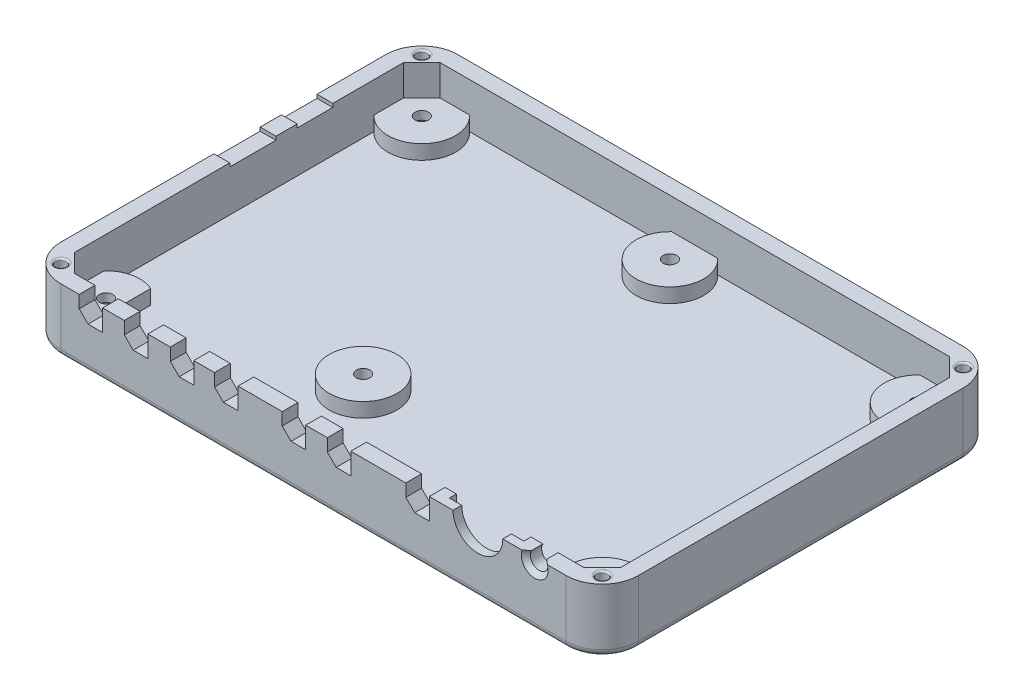
SolidWorks part; units mm, degrees
ref_plane "Front Plane" through (0, 0, 0) normal (0, 0, 1) x (1, 0, 0)
ref_plane "Top Plane" through (0, 0, 0) normal (0, 1, 0) x (1, 0, 0)
ref_plane "Right Plane" through (0, 0, 0) normal (1, 0, 0) x (0, 0, -1)
sketch "Sketch1" plane through (0, 0, 0) normal (0, 1, 0) x (1, 0, 0)
  line L1 (-71.12, 55.88) -> (71.12, 55.88)
  line L2 (-81.28, 45.72) -> (-81.28, -45.72)
  line L3 (-71.12, -55.88) -> (71.12, -55.88)
  line L4 (81.28, 45.72) -> (81.28, -45.72)
  line L5 (-81.28, 55.88) -> (81.28, -55.88) construction
  line L6 (-81.28, -55.88) -> (81.28, 55.88) construction
  arc A0 (-81.28, -45.72) -> (-71.12, -55.88) centre (-71.12, -45.72) ccw
  arc A1 (71.12, -55.88) -> (81.28, -45.72) centre (71.12, -45.72) ccw
  arc A2 (71.12, 55.88) -> (81.28, 45.72) centre (71.12, 45.72) cw
  arc A3 (-71.12, 55.88) -> (-81.28, 45.72) centre (-71.12, 45.72) ccw
  point P0 (0, 0)
  dimension "D3" = 10.16
  dimension "D1" = 162.56
  dimension "D2" = 111.76
extrude "Boss-Extrude1" add sketch "Sketch1" along normal blind 40
sketch "Sketch2" plane through (0, 0, 55.88) normal (0, 0, 1) x (1, 0, 0)
  line L0 (-71.12, 12) -> (71.12, 12) construction
  line L1 (-71.12, 40) -> (-71.12, 0) construction
  line L2 (71.12, 40) -> (71.12, 0) construction
  line L3 (71.12, 18) -> (27.6283, 18) construction
  line L4 (71.12, 28) -> (-71.12, 28) construction
  line L5 (-71.12, 40) -> (71.12, 40) construction
  line L6 (-71.12, 0) -> (71.12, 0) construction
  line L7 (-71.12, 11) -> (71.12, 11) construction
  line L8 (50.798, 16.68) -> (71.12, 16.68) construction
  line L9 (71.12, 9.42) -> (-71.12, 9.42) construction
  line L10 (76.28, 40) -> (76.28, 0) construction
  line L11 (-76.28, 40) -> (-76.28, 0) construction
  line L12 (-81.28, 40) -> (-81.28, 0) construction
  line L13 (81.28, 40) -> (81.28, 0) construction
  line L14 (42.6205, 23.9657) -> (49.9447, 23.9657)
  line L16 (-65.96, 28) -> (-59.356, 28)
  line L17 (-65.96, 28) -> (-65.96, 12)
  line L18 (-65.96, 12) -> (-59.356, 12)
  line L19 (-59.356, 28) -> (-59.356, 12)
  line L20 (-53.26, 28) -> (-46.656, 28)
  line L21 (-53.26, 28) -> (-53.26, 12)
  line L22 (-53.26, 12) -> (-46.656, 12)
  line L23 (-46.656, 28) -> (-46.656, 12)
  line L24 (-40.306, 28) -> (-33.702, 28)
  line L25 (-40.306, 28) -> (-40.306, 12)
  line L26 (-40.306, 12) -> (-33.702, 12)
  line L27 (-33.702, 28) -> (-33.702, 12)
  line L28 (-27.86, 28) -> (-21.256, 28)
  line L29 (-27.86, 28) -> (-27.86, 12)
  line L30 (-27.86, 12) -> (-21.256, 12)
  line L31 (-21.256, 28) -> (-21.256, 12)
  line L32 (-8.81, 28) -> (-2.206, 28)
  line L33 (-8.81, 28) -> (-8.81, 12)
  line L34 (-8.81, 12) -> (-2.206, 12)
  line L35 (-2.206, 28) -> (-2.206, 12)
  line L36 (3.89, 28) -> (10.494, 28)
  line L37 (3.89, 28) -> (3.89, 12)
  line L38 (3.89, 12) -> (10.494, 12)
  line L39 (10.494, 28) -> (10.494, 12)
  line L40 (25.988, 28) -> (32.592, 28)
  line L41 (25.988, 28) -> (25.988, 12)
  line L42 (25.988, 12) -> (32.592, 12)
  line L43 (32.592, 28) -> (32.592, 12)
  circle A0 centre (62.28, 16.68) radius 2.5
  circle A1 centre (46.2826, 18) radius 7 construction
  arc A2 (42.6205, 23.9657) -> (49.9447, 23.9657) centre (46.2826, 18) ccw
  dimension "D9" = 5
  dimension "D11" = 14
  dimension "D1" = 12
  dimension "D2" = 12
  dimension "D3" = 1
  dimension "D4" = 1.58
  dimension "D5" = 7
  dimension "D6" = 5.68
  dimension "D7" = 5
  dimension "D8" = 5
  dimension "D10" = 14
  dimension "D12" = 29.9974
  dimension "D13" = 6.604
  dimension "D14" = 135.636
  dimension "D15" = 6.604
  dimension "D16" = 122.936
  dimension "D17" = 6.604
  dimension "D18" = 109.982
  dimension "D19" = 6.604
  dimension "D20" = 97.536
  dimension "D21" = 6.604
  dimension "D22" = 78.486
  dimension "D23" = 6.604
  dimension "D24" = 65.786
  dimension "D25" = 6.604
  dimension "D26" = 43.688
sketch "Sketch3" plane through (-81.28, 0, 0) normal (-1, 0, 0) x (0, 0, 1)
  line L0 (-55.88, 11) -> (55.88, 11) construction
  line L1 (-55.88, 40) -> (-55.88, 0) construction
  line L2 (55.88, 40) -> (55.88, 0) construction
  line L3 (-45.72, 0) -> (45.72, 0) construction
  line L4 (55.88, 40) -> (55.88, 0) construction
  line L5 (55.88, 9.42) -> (-55.88, 9.42) construction
  line L6 (-50.88, 40) -> (-50.88, 0) construction
  line L7 (-45.72, 40) -> (-55.88, 40) construction
  line L8 (-55.88, 0) -> (-45.72, 0) construction
  line L9 (50.88, 40) -> (50.88, 0) construction
  line L10 (55.88, 40) -> (45.72, 40) construction
  line L11 (45.72, 0) -> (55.88, 0) construction
  line L13 (-26.38, 17) -> (-16.38, 17)
  line L14 (-26.38, 17) -> (-26.38, 29)
  line L15 (-26.38, 29) -> (-16.38, 29)
  line L16 (-16.38, 17) -> (-16.38, 29)
  line L17 (-10.38, 29) -> (2.62, 29)
  line L18 (-10.38, 29) -> (-10.38, 17)
  line L19 (-10.38, 17) -> (2.62, 17)
  line L20 (2.62, 29) -> (2.62, 17)
  dimension "D1" = 5
  dimension "D2" = 5
  dimension "D3" = 9.42
  dimension "D4" = 1.58
  dimension "D5" = 24.5
  dimension "D6" = 6
  dimension "D7" = 12
  dimension "D8" = 10
  dimension "D9" = 6
  dimension "D10" = 13
  dimension "D11" = 12
extrude "Cut-Extrude1" cut sketch "Sketch2" against normal blind 40
extrude "Cut-Extrude2" cut sketch "Sketch3" against normal blind 40
sketch "Sketch4" plane through (0, 0, 55.88) normal (0, 0, 1) x (1, 0, 0)
  line L0 (46.2826, 18) -> (-91.2841, 18)
  line L1 (-91.2841, 18) -> (-91.2841, 53.8224)
  line L2 (-91.2841, 53.8224) -> (88.1928, 53.8224)
  line L3 (88.1928, 53.8224) -> (88.1928, 18)
  line L4 (88.1928, 18) -> (46.2826, 18)
extrude "Cut-Extrude3" cut sketch "Sketch4" against normal blind 120
fillet "Fillet1" radius 2 8 edges at (0, 0, 55.88) (78.3042, 0, 52.9042) (81.28, 0, 0) (78.3042, 0, -52.9042) (0, 0, -55.88) (-78.3042, 0, -52.9042) (-81.28, 0, 0) (-78.3042, 0, 52.9042)
sketch "Sketch5" plane through (0, 18, 0) normal (0, 1, 0) x (1, 0, 0)
  line L0 (-76.835, -46.355) -> (-71.755, -51.435)
  line L1 (-71.755, 51.435) -> (71.755, 51.435)
  line L2 (-76.835, 46.355) -> (-76.835, -46.355)
  line L3 (-71.755, -51.435) -> (71.755, -51.435)
  line L4 (76.835, 46.355) -> (76.835, -46.355)
  line L5 (-76.835, 51.435) -> (76.835, -51.435) construction
  line L6 (-76.835, -51.435) -> (76.835, 51.435) construction
  line L7 (-76.835, 46.355) -> (-71.755, 51.435)
  line L8 (71.755, 51.435) -> (76.835, 46.355)
  line L9 (71.755, -51.435) -> (76.835, -46.355)
  point P0 (0, 0)
  dimension "D1" = 153.67
  dimension "D2" = 102.87
  dimension "D5" = 5.08
  dimension "D6" = 5.08
  dimension "D7" = 5.08
  dimension "D8" = 5.08
extrude "Cut-Extrude4" cut sketch "Sketch5" against normal blind 12.7
sketch "Sketch6" plane through (0, 5.3, 0) normal (0, 1, 0) x (1, 0, 0)
  line L0 (-76.835, 46.355) -> (-76.835, 26.38) construction
  line L1 (71.755, 51.435) -> (-71.755, 51.435) construction
  line L2 (71.755, 51.435) -> (-71.755, 51.435) construction
  line L3 (76.835, -46.355) -> (76.835, 46.355) construction
  line L4 (71.755, -51.435) -> (64.4031, -51.435) construction
  line L5 (-71.755, -51.435) -> (-65.96, -51.435) construction
  line L6 (-76.835, -46.355) -> (-76.835, -2.62) construction
  circle A0 centre (-69.85, -44.45) radius 9.525
  circle A1 centre (-69.85, 44.45) radius 9.525
  circle A2 centre (0, 44.45) radius 9.525
  circle A3 centre (69.85, 44.45) radius 9.525
  circle A4 centre (-15.24, -26.67) radius 9.525
  circle A5 centre (69.85, -44.45) radius 9.525
  point P22 (-68.8575, -51.435)
  dimension "D3" = 19.05
  dimension "D6" = 19.05
  dimension "D9" = 19.05
  dimension "D12" = 19.05
  dimension "D17" = 19.05
  dimension "D18" = 19.05
  dimension "D1" = 6.985
  dimension "D2" = 6.985
  dimension "D4" = 6.985
  dimension "D5" = 76.835
  dimension "D7" = 6.985
  dimension "D8" = 6.985
  dimension "D10" = 6.985
  dimension "D11" = 6.985
  dimension "D13" = 78.105
  dimension "D14" = 92.075
  dimension "D15" = 6.985
  dimension "D16" = 6.985
extrude "Boss-Extrude2" add sketch "Sketch6" along normal blind 4.064
sketch "Sketch7" plane through (0, 9.364, 0) normal (0, 1, 0) x (1, 0, 0)
  line L1 (-65.96, -51.435) -> (-54.2836, -51.435)
  line L2 (-65.96, -51.435) -> (-65.96, -28.2347)
  line L3 (-65.96, -28.2347) -> (-54.2836, -28.2347)
  line L4 (-54.2836, -51.435) -> (-54.2836, -28.2347)
extrude "Cut-Extrude5" cut sketch "Sketch7" against normal blind 4.064
sketch "Sketch8" plane through (0, 9.364, 0) normal (0, 1, 0) x (1, 0, 0)
  circle A0 centre (-69.85, 44.45) radius 1.905
  circle A1 centre (0, 44.45) radius 1.905
  circle A2 centre (69.85, 44.45) radius 1.905
  circle A3 centre (69.85, -44.45) radius 1.905
  circle A4 centre (-15.24, -26.67) radius 1.905
  circle A5 centre (-69.85, -44.45) radius 1.905
  dimension "D1" = 3.81
  dimension "D2" = 3.81
  dimension "D3" = 3.81
  dimension "D4" = 3.81
  dimension "D5" = 3.81
  dimension "D6" = 3.81
extrude "Cut-Extrude6" cut sketch "Sketch8" against normal blind 14.224
sketch "Sketch9" plane through (0, 0, 0) normal (0, -1, 0) x (1, 0, 0)
  circle A0 centre (-69.85, 44.45) radius 3.25
  circle A2 centre (69.85, 44.45) radius 3.25
  circle A3 centre (69.85, -44.45) radius 3.25
  circle A5 centre (-69.85, -44.45) radius 3.25
  dimension "D1" = 6.5
  dimension "D3" = 6.5
  dimension "D4" = 6.5
  dimension "D6" = 6.5
extrude "Cut-Extrude7" cut sketch "Sketch9" against normal blind 7
chamfer "Chamfer1" distance 1.27 angle 45 1 edges at (62.28, 14.18, 55.88)
sketch "Sketch11" plane through (0, 18, 0) normal (0, 1, 0) x (1, 0, 0)
  line L0 (-81.28, 26.38) -> (-81.28, 45.72) construction
  line L1 (-71.12, 55.88) -> (71.12, 55.88) construction
  circle A0 centre (-76.2, 50.8) radius 1.524
  dimension "D1" = 3.048
  dimension "D2" = 5.08
  dimension "D3" = 5.08
extrude "Cut-Extrude8" cut sketch "Sketch11" against normal blind 3
mirror "Mirror1" about plane through (0, 0, 0) normal (0, 0, 1) of "Cut-Extrude8"
mirror "Mirror2" about plane through (0, 0, 0) normal (1, 0, 0) of "Cut-Extrude8", "Mirror1"
fillet "Fillet2" radius 0.508 4 edges at (76.2, 18, -49.276) (76.2, 18, 49.276) (-76.2, 18, -49.276) (-76.2, 18, 49.276)
chamfer "Chamfer2" distance 2.5 angle 45 7 edges at (25.988, 12, 53.6575) (3.89, 12, 53.6575) (-8.81, 12, 53.6575) (-27.86, 12, 53.6575) (-40.306, 12, 53.6575) (-53.26, 12, 53.6575) (-65.96, 12, 53.6575)
sketch "Sketch12" plane through (0, 18, 0) normal (0, 1, 0) x (1, 0, 0)
  line L0 (-76.835, 37.9742) -> (-76.835, -37.9742) construction
  line L1 (-69.335, 53.935) -> (69.335, 53.935)
  line L2 (-79.335, 43.935) -> (-79.335, -43.935)
  line L3 (-69.335, -53.935) -> (69.335, -53.935)
  line L4 (79.335, 43.935) -> (79.335, -43.935)
  line L5 (-79.335, 53.935) -> (79.335, -53.935) construction
  line L6 (-79.335, -53.935) -> (79.335, 53.935) construction
  line L7 (71.755, 51.435) -> (-71.755, 51.435) construction
  line L8 (-79.335, 43.935) -> (-69.335, 53.935)
  line L9 (69.335, 53.935) -> (79.335, 43.935)
  line L10 (69.335, -53.935) -> (79.335, -43.935)
  line L11 (-79.335, -43.935) -> (-69.335, -53.935)
  point P0 (0, 0)
  dimension "D1" = 2.5
  dimension "D2" = 2.5
  dimension "D9" = 10
  dimension "D10" = 10
  dimension "D11" = 10
  dimension "D12" = 10
extrude "Cut-Extrude9" [suppressed] cut sketch "Sketch12" against normal blind 2.5
sketch "Sketch13" plane through (0, 0, 51.435) normal (0, 0, -1) x (-1, 0, 0)
  line L1 (-56.7826, 28.5) -> (-35.7826, 28.5)
  line L2 (-56.7826, 28.5) -> (-56.7826, 7.5)
  line L3 (-56.7826, 7.5) -> (-35.7826, 7.5)
  line L4 (-35.7826, 28.5) -> (-35.7826, 7.5)
  line L5 (-56.7826, 28.5) -> (-35.7826, 7.5) construction
  line L6 (-56.7826, 7.5) -> (-35.7826, 28.5) construction
  point P0 (-46.2826, 18)
  dimension "D1" = 21
  dimension "D2" = 21
extrude "Cut-Extrude10" cut sketch "Sketch13" against normal blind 2
sketch "Sketch14" plane through (0, 0, 0) normal (0, -1, 0) x (1, 0, 0)
  line L1 (-13.1034, 23.7264) -> (-11.6224, 27.0485)
  line L2 (-11.6224, 27.0485) -> (-13.759, 29.9922)
  line L3 (-13.759, 29.9922) -> (-17.3766, 29.6136)
  line L4 (-17.3766, 29.6136) -> (-18.8576, 26.2915)
  line L5 (-18.8576, 26.2915) -> (-16.721, 23.3478)
  line L6 (-16.721, 23.3478) -> (-13.1034, 23.7264)
  line L7 (2.9276, -46.6085) -> (3.3331, -42.9939)
  line L8 (3.3331, -42.9939) -> (0.4055, -40.8354)
  line L9 (0.4055, -40.8354) -> (-2.9276, -42.2915)
  line L10 (-2.9276, -42.2915) -> (-3.3331, -45.9061)
  line L11 (-3.3331, -45.9061) -> (-0.4055, -48.0646)
  line L12 (-0.4055, -48.0646) -> (2.9276, -46.6085)
  circle A0 centre (-15.24, 26.67) radius 3.15 construction
  circle A1 centre (0, -44.45) radius 3.15 construction
  dimension "D1" = 6.3
  dimension "D2" = 6.3
extrude "Cut-Extrude11" cut sketch "Sketch14" against normal blind 2.54
